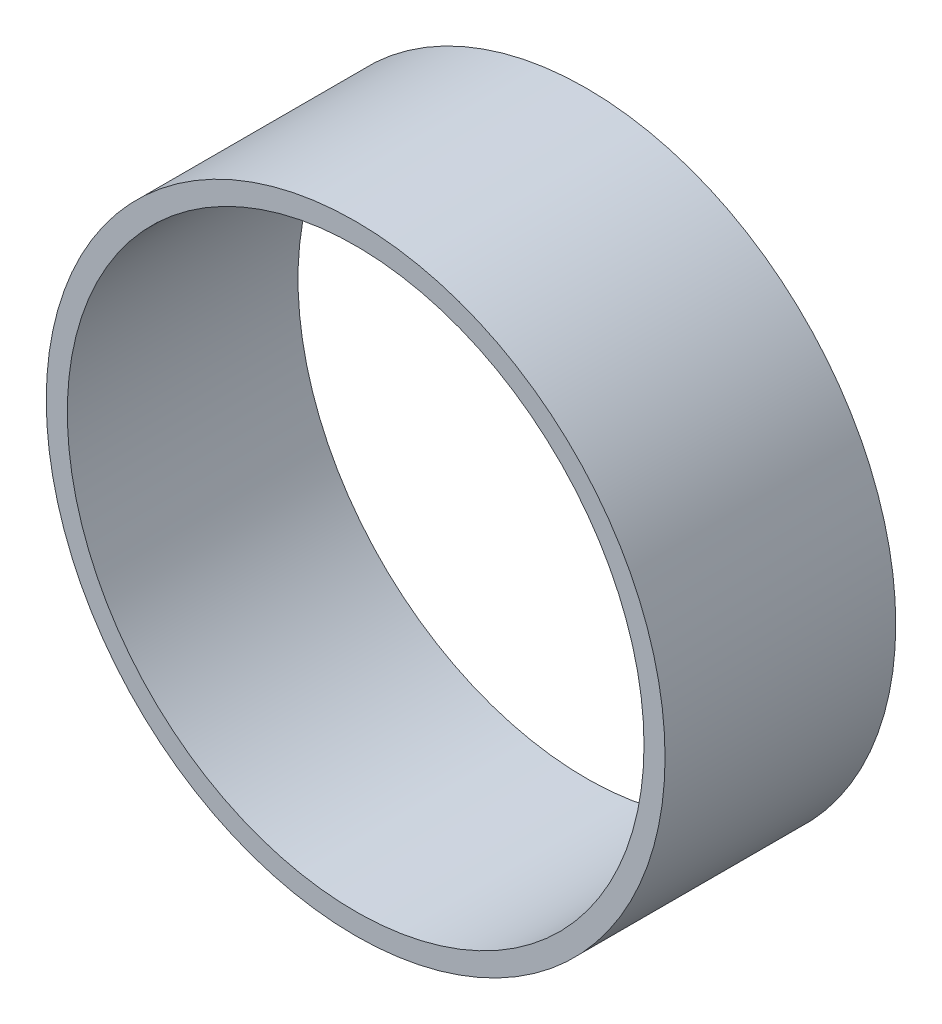
SolidWorks part; units mm, degrees
material "PVC 0.007 Plasticized"
ref_plane "Front Plane" through (0, 0, 0) normal (0, 0, 1) x (1, 0, 0)
ref_plane "Top Plane" through (0, 0, 0) normal (0, 1, 0) x (1, 0, 0)
ref_plane "Right Plane" through (0, 0, 0) normal (1, 0, 0) x (0, 0, -1)
sketch "Sketch1" plane through (0, 0, 0) normal (0, 0, 1) x (1, 0, 0)
  circle A0 centre (0, 0) radius 136.271
  circle A1 centre (0, 0) radius 127
  dimension "D1" = 9.271
  dimension "D2" = 254
extrude "Boss-Extrude1" add sketch "Sketch1" along normal blind 101.6
